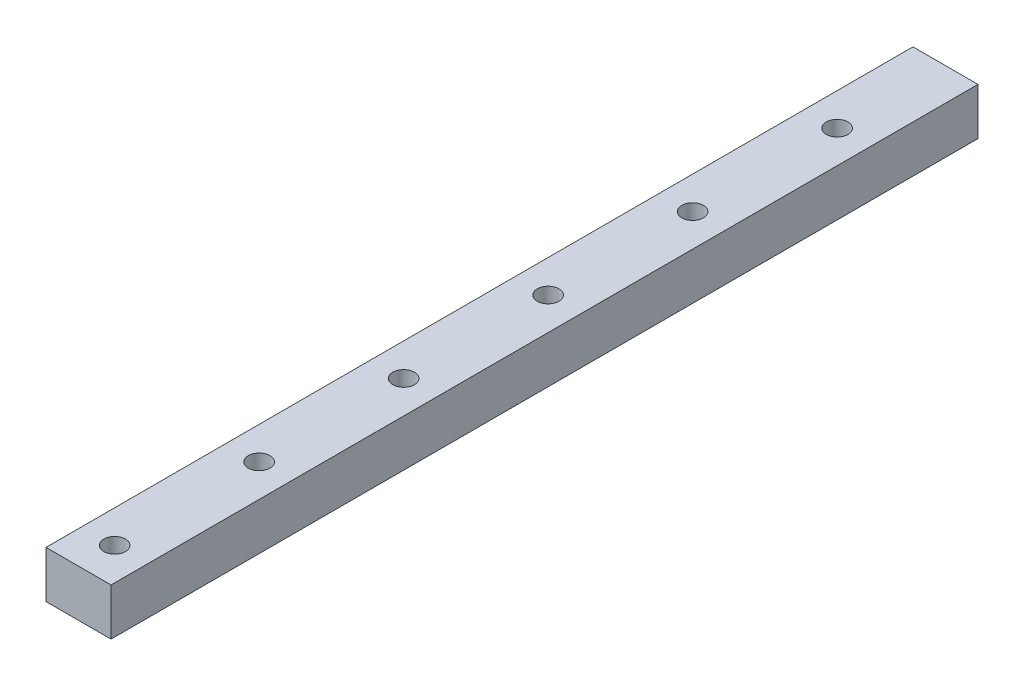
SolidWorks part; units mm, degrees
ref_plane "前视基准面" through (0, 0, 0) normal (0, 0, 1) x (1, 0, 0)
ref_plane "上视基准面" through (0, 0, 0) normal (0, 1, 0) x (1, 0, 0)
ref_plane "右视基准面" through (0, 0, 0) normal (1, 0, 0) x (0, 0, -1)
other "Configuration Table"
sketch "草图1" plane through (0, 0, 0) normal (0, 0, 1) x (1, 0, 0)
  line L1 (0, 0) -> (9, 0)
  line L2 (0, 0) -> (0, 6.5)
  line L3 (0, 6.5) -> (9, 6.5)
  line L4 (9, 0) -> (9, 6.5)
  dimension "D1" = 9
  dimension "D2" = 6.5
extrude "凸台-拉伸1" add sketch "草图1" along normal blind 120
sketch "草图2" plane through (0, 6.5, 0) normal (0, 1, 0) x (1, 0, 0)
  line L0 (0, -120) -> (0, 0) construction
  line L1 (9, -120) -> (0, -120) construction
  circle A0 centre (4.5, -115) radius 1.5
  circle A1 centre (4.5, -95) radius 1.5
  circle A2 centre (4.5, -75) radius 1.5
  circle A3 centre (4.5, -55) radius 1.5
  circle A4 centre (4.5, -35) radius 1.5
  circle A5 centre (4.5, -15) radius 1.5
  dimension "D1" = 3
  dimension "D2" = 4.5
  dimension "D3" = 5
  dimension "D5" = 20
  dimension "D4" = 6
extrude "切除-拉伸1" cut sketch "草图2" against normal blind 100
